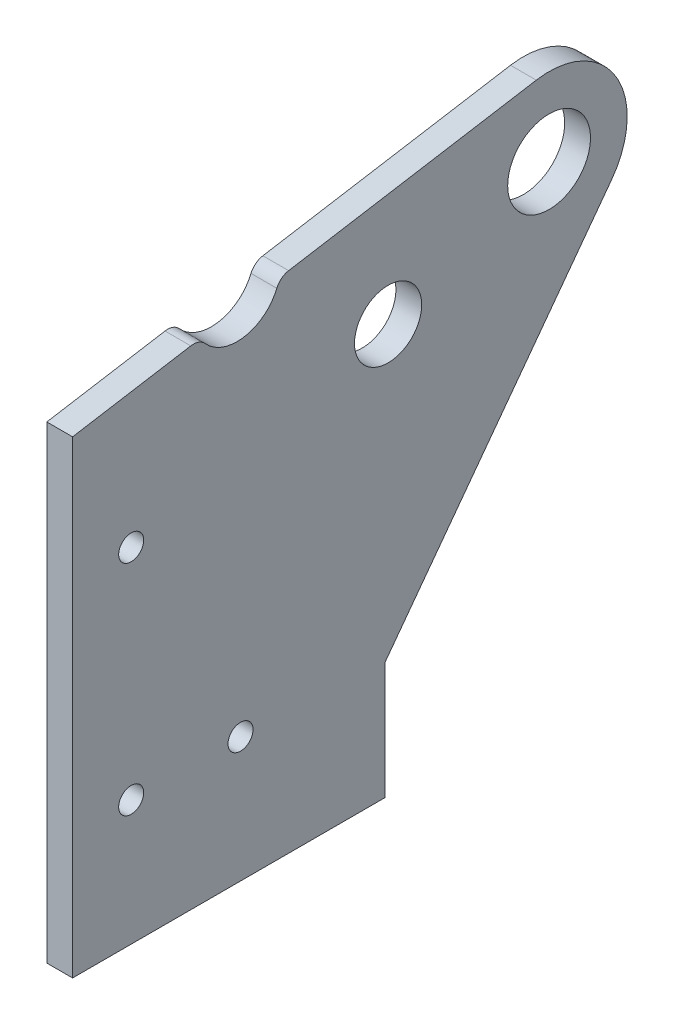
SolidWorks part; units mm, degrees
ref_plane "Front" through (0, 0, 0) normal (0, 0, 1) x (1, 0, 0)
ref_plane "Top" through (0, 0, 0) normal (0, 1, 0) x (1, 0, 0)
ref_plane "Right" through (0, 0, 0) normal (1, 0, 0) x (0, 0, -1)
sketch "Sketch1" plane through (-39, 0, 0) normal (-1, 0, 0) x (0, 0, 1)
  line L2 (61, 0) -> (21, 0)
  line L3 (61, 60) -> (61, 0)
  line L6 (-8.0246, 54.033) -> (21, 15)
  line L7 (61, 60) -> (1.6393, 69.8647)
  line L8 (21, 15) -> (21, 0)
  line L9 (-65, 60) -> (65, 60) construction
  line L10 (61, 0) -> (31, 0) construction
  line L11 (65, -6) -> (65, 60) construction
  circle A11 centre (20.6096, 52.3031) radius 4.3
  circle A12 centre (20.6096, 52.3031) radius 4.3
  arc A13 (-8.0246, 54.033) -> (1.6393, 69.8647) centre (0, 60) cw
  circle A14 centre (0, 60) radius 5.3
  circle A15 centre (0, 60) radius 5.3
  dimension "D5" = 10
  dimension "D3" = 40
  dimension "D4" = 15
  dimension "D6" = 4
  dimension "D1" = 0.3
  dimension "D2" = 0.3
extrude "Boss-Extrude1" add sketch "Sketch1" along normal offset from surface (3.3 mm away) 0.3
sketch "Sketch2" plane through (-42.3, 0, 0) normal (-1, 0, 0) x (0, 0, 1)
  circle A3 centre (39.9311, 65.5231) radius 5.5
  circle A4 centre (39.9311, 65.5231) radius 5.5
  dimension "D1" = 4
extrude "Cut-Extrude1" cut sketch "Sketch2" against normal through all contours A4
fillet "Fillet1" radius 2 2 edges at (-40.65, 64.3959, 34.5479) (-40.65, 62.7154, 44.6604)
sketch "Sketch3" plane through (-39, 0, 0) normal (1, 0, 0) x (0, 0, -1)
  circle A0 centre (-53.5, 44) radius 1.6 construction
  circle A1 centre (-39.5, 16) radius 1.6 construction
  circle A2 centre (-53.5, 16) radius 1.6 construction
  circle A3 centre (-53.5, 44) radius 1.6
  circle A4 centre (-39.5, 16) radius 1.6
  circle A5 centre (-53.5, 16) radius 1.6
extrude "Cut-Extrude2" cut sketch "Sketch3" against normal through all
